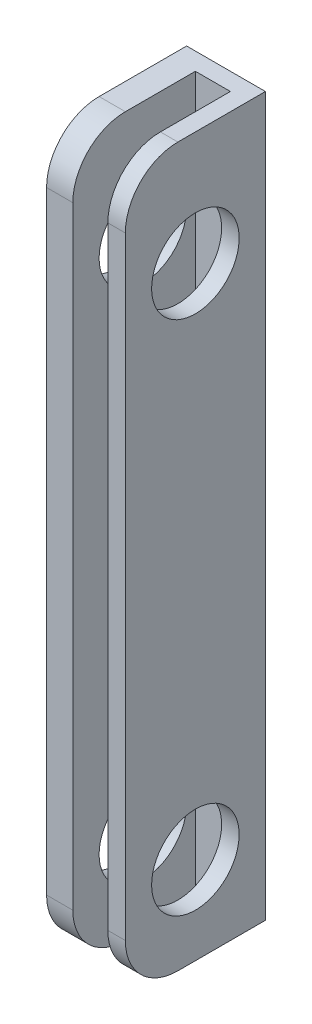
SolidWorks part; units mm, degrees
ref_plane "Спереди" through (0, 0, 0) normal (0, 0, 1) x (1, 0, 0)
ref_plane "Сверху" through (0, 0, 0) normal (0, 1, 0) x (1, 0, 0)
ref_plane "Справа" through (0, 0, 0) normal (1, 0, 0) x (0, 0, -1)
sketch "Эскиз1" plane through (0, 0, 0) normal (0, 0, 1) x (1, 0, 0)
  line L1 (-2.25, 20.5) -> (2.25, 20.5)
  line L2 (-2.25, 20.5) -> (-2.25, -20.5)
  line L3 (-2.25, -20.5) -> (2.25, -20.5)
  line L4 (2.25, 20.5) -> (2.25, -20.5)
  line L5 (-2.25, 20.5) -> (2.25, -20.5) construction
  line L6 (-2.25, -20.5) -> (2.25, 20.5) construction
  point P0 (0, 0)
  point P8 (-6.1583, 26.6073)
  dimension "D1" = 4.5
  dimension "41" = 41
extrude "Бобышка-Вытянуть1" add sketch "Эскиз1" along normal blind 8
sketch "Эскиз3" plane through (0, 0, 8) normal (0, 0, 1) x (1, 0, 0)
  line L0 (2.25, 20.5) -> (-2.25, 20.5) construction
  line L1 (-0.75, 20.5) -> (1.25, 20.5)
  line L2 (-0.75, 20.5) -> (-0.75, -20.5)
  line L3 (-0.75, -20.5) -> (1.25, -20.5)
  line L4 (1.25, 20.5) -> (1.25, -20.5)
  line L5 (-2.25, -20.5) -> (2.25, -20.5) construction
  dimension "D1" = 1.5
  dimension "D2" = 1
extrude "Вырез-Вытянуть1" cut sketch "Эскиз3" against normal blind 7
sketch "Эскиз5" plane through (2.25, 0, 0) normal (1, 0, 0) x (0, 0, -1)
  line L0 (-16.3198, 14) -> (15.9268, 14) construction
  line L1 (-4, 24.6076) -> (-4, 5.2464) construction
  line L2 (-4, 5.2464) -> (-4, -24.8262) construction
  line L3 (-10.9542, -15.5) -> (9.266, -15.5) construction
  circle A0 centre (-4, 14) radius 2.5
  circle A1 centre (-4, -15.5) radius 2.5
  dimension "D1" = 6.5
  dimension "D2" = 4
  dimension "D3" = 5
extrude "Вырез-Вытянуть2" cut sketch "Эскиз5" against normal through all
fillet "Скругление1" radius 3 4 edges at (-1.5, -20.5, 8) (1.75, -20.5, 8) (-1.5, 20.5, 8) (1.75, 20.5, 8)
